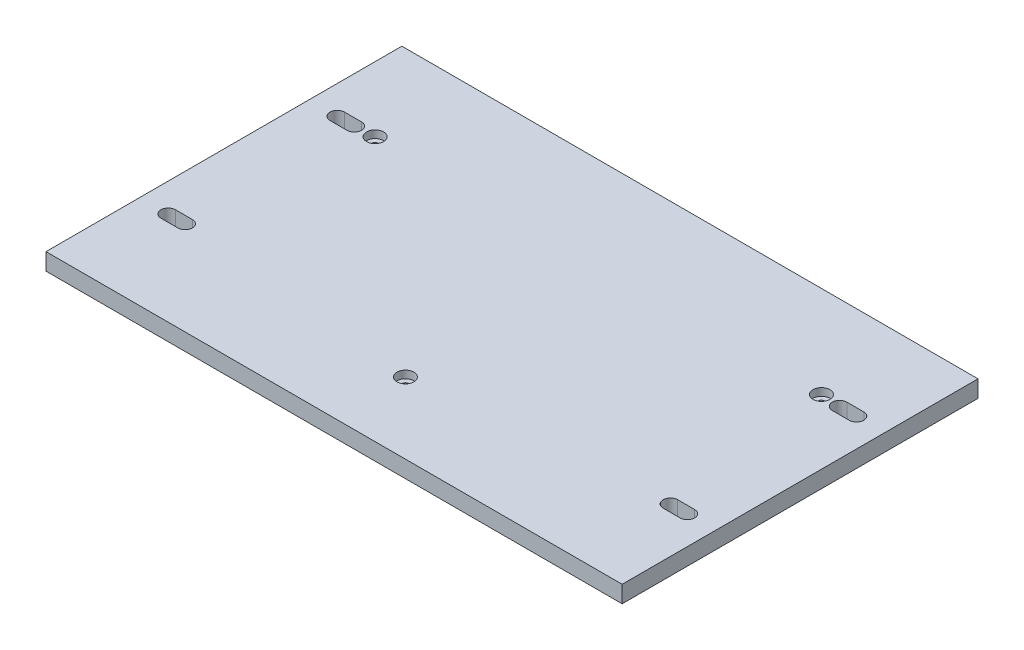
SolidWorks part; units mm, degrees
ref_plane "Front Plane" through (0, 0, 0) normal (0, 0, 1) x (1, 0, 0)
ref_plane "Top Plane" through (0, 0, 0) normal (0, 1, 0) x (1, 0, 0)
ref_plane "Right Plane" through (0, 0, 0) normal (1, 0, 0) x (0, 0, -1)
sketch "Sketch1" plane through (0, 0, 0) normal (0, 1, 0) x (1, 0, 0)
  line L0 (0, 133.35) -> (0, -133.35) construction
  line B0 (215.9, -133.35) -> (215.9, 133.35)
  line B1 (215.9, 133.35) -> (-215.9, 133.35)
  line B2 (-215.9, 133.35) -> (-215.9, -133.35)
  line B3 (-215.9, -133.35) -> (215.9, -133.35)
  line B4 (-194.564, 58.166) -> (-181.864, 58.166)
  line B5 (-181.864, 69.088) -> (-194.564, 69.088)
  line B6 (-181.864, -57.658) -> (-194.564, -57.658)
  line B7 (-194.564, -68.58) -> (-181.864, -68.58)
  line B8 (194.564, 69.088) -> (181.864, 69.088)
  line B9 (181.864, 58.166) -> (194.564, 58.166)
  line B10 (181.864, -68.58) -> (194.564, -68.58)
  line B11 (194.564, -57.658) -> (181.864, -57.658)
  arc B12 (-181.864, 58.166) -> (-181.864, 69.088) centre (-181.864, 63.627) ccw
  arc B13 (-194.564, 69.088) -> (-194.564, 58.166) centre (-194.564, 63.627) ccw
  arc B14 (-181.864, -68.58) -> (-181.864, -57.658) centre (-181.864, -63.119) ccw
  arc B15 (-194.564, -57.658) -> (-194.564, -68.58) centre (-194.564, -63.119) ccw
  arc B16 (194.564, 58.166) -> (194.564, 69.088) centre (194.564, 63.627) ccw
  arc B17 (181.864, 69.088) -> (181.864, 58.166) centre (181.864, 63.627) ccw
  arc B18 (194.564, -68.58) -> (194.564, -57.658) centre (194.564, -63.119) ccw
  arc B19 (181.864, -57.658) -> (181.864, -68.58) centre (181.864, -63.119) ccw
  arc B20 (-167.132, 67.2835) -> (-167.132, 61.7375) centre (-167.132, 64.5105) ccw
  arc B21 (-167.132, 61.7375) -> (-167.132, 67.2835) centre (-167.132, 64.5105) ccw
  arc B22 (0.168, -77.2725) -> (0.168, -82.7725) centre (0.168, -80.0225) ccw
  arc B23 (0.168, -82.7725) -> (0.168, -77.2725) centre (0.168, -80.0225) ccw
  arc B24 (167.428, 67.3235) -> (167.428, 61.6975) centre (167.428, 64.5105) ccw
  arc B25 (167.428, 61.6975) -> (167.428, 67.3235) centre (167.428, 64.5105) ccw
sketch_block_instance "Block1-1"
sketch_block "Block1"
extrude "Extrude1" add sketch "Sketch1" along normal blind 12.7
sketch "Sketch2" plane through (0, 12.7, 0) normal (0, 1, 0) x (1, 0, 0)
  circle A0 centre (-167.132, 64.5105) radius 6.35
  circle A1 centre (0.168, -80.0225) radius 6.35
  circle A2 centre (167.428, 64.5105) radius 6.35
  dimension "D1" = 12.7
  dimension "D2" = 12.7
  dimension "D3" = 12.7
extrude "Extrude2" cut sketch "Sketch2" against normal blind 5.6642
